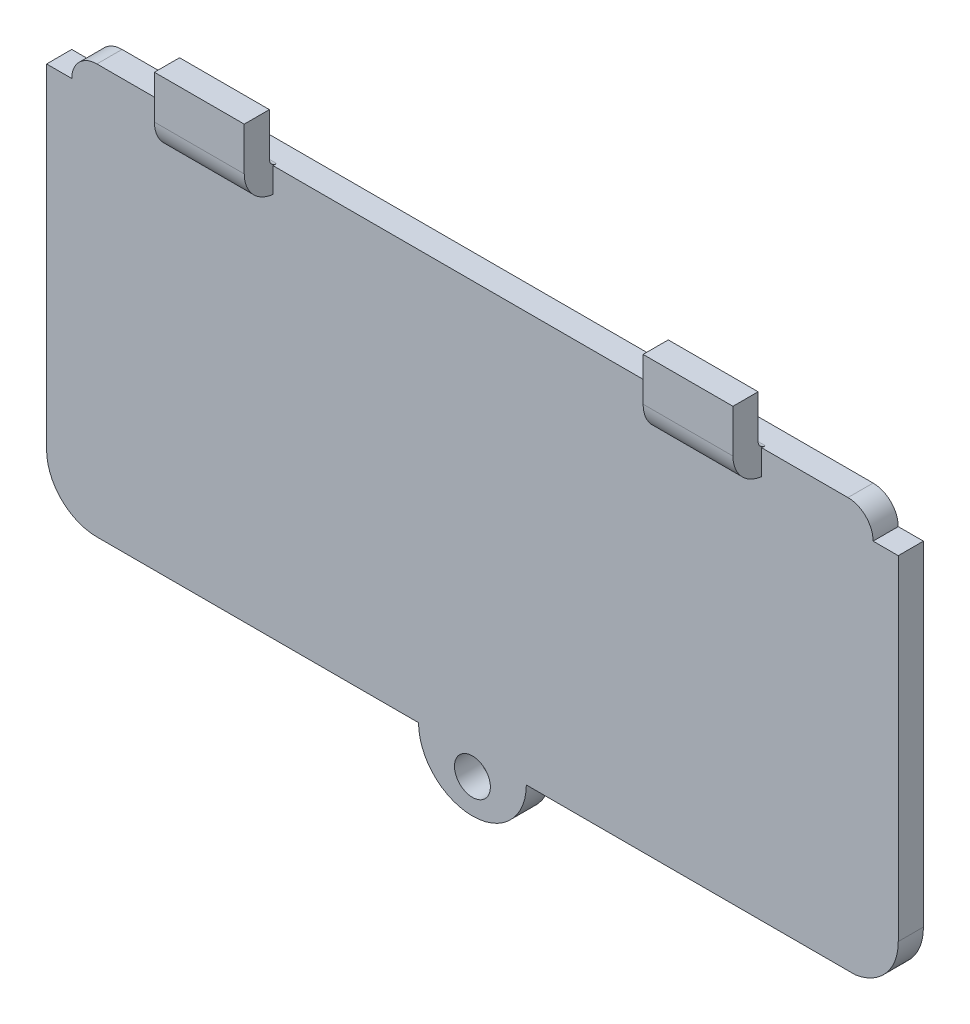
SolidWorks part; units mm, degrees
ref_plane "Front Plane" through (0, 0, 0) normal (0, 0, 1) x (1, 0, 0)
ref_plane "Top Plane" through (0, 0, 0) normal (0, 1, 0) x (1, 0, 0)
ref_plane "Right Plane" through (0, 0, 0) normal (1, 0, 0) x (0, 0, -1)
sketch "Sketch1" plane through (0, 0, 0) normal (0, 0, 1) x (1, 0, 0)
  line L0 (-30.353, 12.065) -> (-30.353, -11.557)
  line L1 (-26.797, 13.843) -> (26.289, 13.843)
  line L5 (3.556, -15.113) -> (26.797, -15.113)
  line L7 (-26.797, -15.113) -> (-4.064, -15.113)
  line L8 (29.845, 12.065) -> (29.845, -11.557)
  line L9 (-30.353, 12.065) -> (-28.575, 12.065)
  line L10 (28.067, 12.065) -> (29.845, 12.065)
  line L12 (27.3468, 13.4941) -> (28.067, 13.843) construction
  arc A0 (26.289, 13.843) -> (28.067, 12.065) centre (26.289, 12.065) cw
  arc A3 (-26.797, 13.843) -> (-28.575, 12.065) centre (-26.797, 12.065) ccw
  arc A4 (-30.353, -11.557) -> (-26.797, -15.113) centre (-26.797, -11.557) ccw
  arc A5 (26.797, -15.113) -> (29.845, -11.557) centre (26.2892, -11.5934) ccw
  arc A6 (-4.064, -15.113) -> (3.556, -15.113) centre (-0.254, -15.113) ccw
  point P0 (0, 0)
  dimension "D3" = 1.778
  dimension "D6" = 7.62
  dimension "D1" = 28.956
  dimension "D2" = 60.198
  dimension "D4" = 27.178
  dimension "D5" = 27.178
extrude "Boss-Extrude1" add sketch "Sketch1" along normal blind 1.778
sketch "Sketch3" plane through (0, 0, 0) normal (0, 0, -1) x (-1, 0, 0)
  circle A0 centre (0.254, -16.51) radius 1.27
extrude "Cut-Extrude1" cut sketch "Sketch3" against normal blind 1.778
sketch "Sketch5" plane through (0, 0, 1.778) normal (0, 0, 1) x (1, 0, 0)
  line L0 (-20.701, 14.097) -> (-20.701, 10.0714)
ref_plane "Plane2" through (-20.701, 0, 0) normal (-1, 0, 0) x (0, 0, 1)
sketch "Sketch7" plane through (-20.701, 0, 0) normal (-1, 0, 0) x (0, 0, 1)
  line L1 (2.032, 14.351) -> (2.032, 17.399)
  line L7 (3.81, 14.351) -> (3.81, 17.399)
  line L8 (2.032, 17.399) -> (3.81, 17.399)
  line L9 (1.524, 13.843) -> (1.524, 12.065)
  arc A0 (1.524, 13.843) -> (2.032, 14.351) centre (1.524, 14.351) ccw
  arc A2 (1.524, 12.065) -> (3.81, 14.351) centre (1.524, 14.351) ccw
  point P11 (2.032, 13.843)
  point P14 (3.81, 13.5772)
  dimension "D6" = 0.508
  dimension "D1" = 1.778
  dimension "D2" = 3.048
extrude "Boss-Extrude2" add sketch "Sketch7" against normal blind 40.894
sketch "Sketch8" plane through (0, 0, 1.778) normal (0, 0, 1) x (1, 0, 0)
  line L0 (20.193, 17.399) -> (-20.701, 17.399) construction
  line L1 (-14.351, 17.399) -> (13.843, 17.399)
  line L2 (-14.351, 17.399) -> (-14.351, 13.843)
  line L3 (-14.351, 13.843) -> (13.843, 13.843)
  line L4 (13.843, 17.399) -> (13.843, 13.843)
  line L6 (20.193, 13.843) -> (-20.701, 13.843) construction
extrude "Cut-Extrude3" cut sketch "Sketch8" against normal mid plane 6.35
sketch "Sketch10" plane through (0, -15.113, 0) normal (0, -1, 0) x (1, 0, 0)
  line L0 (3.556, 1.778) -> (26.797, 1.778) construction
  line L1 (-14.351, 3.7528) -> (13.843, 3.7528)
  line L2 (-14.351, 3.7528) -> (-14.351, 1.778)
  line L3 (-14.351, 1.778) -> (13.843, 1.778)
  line L4 (13.843, 3.7528) -> (13.843, 1.778)
  line L5 (13.843, 1.524) -> (13.843, 3.7528) construction
extrude "Cut-Extrude4" cut sketch "Sketch10" against normal blind 31.75
